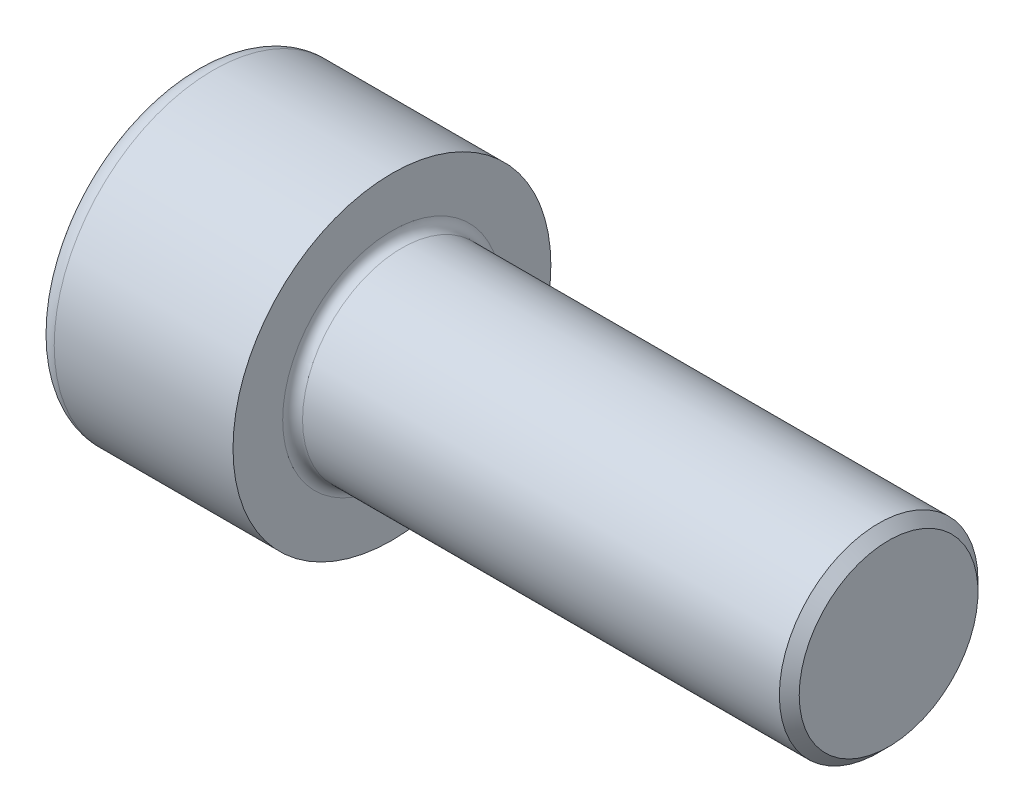
SolidWorks part; units mm, degrees
ref_plane "Alzado" through (0, 0, 0) normal (0, 0, 1) x (1, 0, 0)
ref_plane "Planta" through (0, 0, 0) normal (0, 1, 0) x (1, 0, 0)
ref_plane "Vista lateral" through (0, 0, 0) normal (1, 0, 0) x (0, 0, -1)
sketch "Croquis1" plane through (0, 0, 0) normal (0, 0, 1) x (1, 0, 0)
  line L0 (0, 0) -> (0, 8)
  line L1 (0, 8) -> (10, 8)
  line L2 (10, 8) -> (10, 5)
  line L3 (10, 5) -> (35, 5)
  line L4 (35, 5) -> (35, 0)
  line L5 (35, 0) -> (0, 0)
  line L6 (0, 0) -> (88.0126, 0) construction
  dimension "D1" = 16
  dimension "D2" = 10
  dimension "D3" = 10
  dimension "D4" = 35
revolve "Revolución1" add sketch "Croquis1" angle 360 about L6
sketch "Croquis2" plane through (0, 0, 0) normal (-1, 0, 0) x (0, 0, 1)
  line L1 (0, 4.6188) -> (-4, 2.3094)
  line L2 (-4, 2.3094) -> (-4, -2.3094)
  line L3 (-4, -2.3094) -> (0, -4.6188)
  line L4 (0, -4.6188) -> (4, -2.3094)
  line L5 (4, -2.3094) -> (4, 2.3094)
  line L6 (4, 2.3094) -> (0, 4.6188)
  circle A0 centre (0, 0) radius 4 construction
  dimension "D1" = 8
extrude "Cortar-Extruir1" cut sketch "Croquis2" against normal blind 5
fillet "Redondeo1" radius 1 1 edges at (0, 0, 8)
fillet "Redondeo2" radius 0.5 1 edges at (10, 0, 5)
chamfer "Chaflán1" distance 0.5 angle 45 1 edges at (35, 0, 5)
